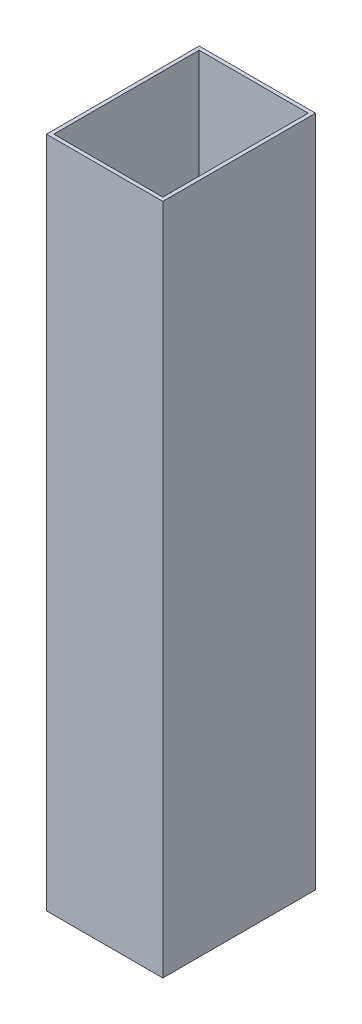
SolidWorks part; units mm, degrees
material "1060 Alloy"
ref_plane "Front Plane" through (0, 0, 0) normal (0, 0, 1) x (1, 0, 0)
ref_plane "Top Plane" through (0, 0, 0) normal (0, 1, 0) x (1, 0, 0)
ref_plane "Right Plane" through (0, 0, 0) normal (1, 0, 0) x (0, 0, -1)
sketch "Sketch1" plane through (0, 0, 0) normal (0, 1, 0) x (1, 0, 0)
  line L1 (-27.3922, -18.9255) -> (48.8078, -18.9255)
  line L2 (-27.3922, -18.9255) -> (-27.3922, -120.5255)
  line L3 (-27.3922, -120.5255) -> (48.8078, -120.5255)
  line L4 (48.8078, -18.9255) -> (48.8078, -120.5255)
  dimension "D1" = 76.2
  dimension "D2" = 101.6
extrude "Extrude-Thin1" add sketch "Sketch1" along normal blind 469.9 thin thin type one direction wall 2.54
